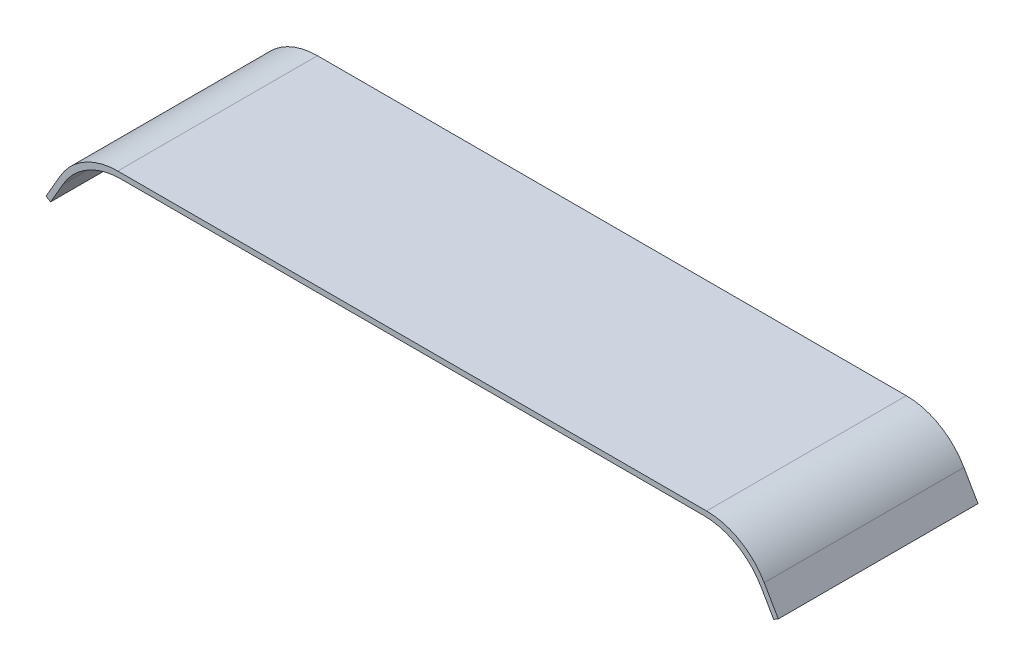
SolidWorks part; units mm, degrees
ref_plane "Front Plane" through (0, 0, 0) normal (0, 0, 1) x (1, 0, 0)
ref_plane "Top Plane" through (0, 0, 0) normal (0, 1, 0) x (1, 0, 0)
ref_plane "Right Plane" through (0, 0, 0) normal (1, 0, 0) x (0, 0, -1)
sketch "Sketch1" plane through (0, 0, 0) normal (0, 0, 1) x (1, 0, 0)
  line L0 (0, 0) -> (0.4769, 0.826)
  line L1 (0.4769, 0.826) -> (10.3845, 0.826)
  line L2 (10.3845, 0.826) -> (10.8614, 0)
  line L3 (10.8614, 0) -> (10.9307, 0.04)
  line L4 (10.9307, 0.04) -> (10.4307, 0.906)
  line L5 (10.4307, 0.906) -> (0.4307, 0.906)
  line L6 (0.4307, 0.906) -> (-0.0693, 0.04)
  line L7 (-0.0693, 0.04) -> (0, 0)
  point P3 (10.6388, 0)
  dimension "D1" = 0.08
  dimension "D2" = 10
  dimension "D3" = 0.08
  dimension "D4" = 0.08
  dimension "D5" = 120
  dimension "D6" = 120
  dimension "D7" = 1
  dimension "D8" = 1
extrude "Boss-Extrude1" add sketch "Sketch1" along normal blind 3
fillet "Fillet1" radius 1 4 edges at (0.4769, 0.826, 1.5) (0.4307, 0.906, 1.5) (10.4307, 0.906, 1.5) (10.3845, 0.826, 1.5)
